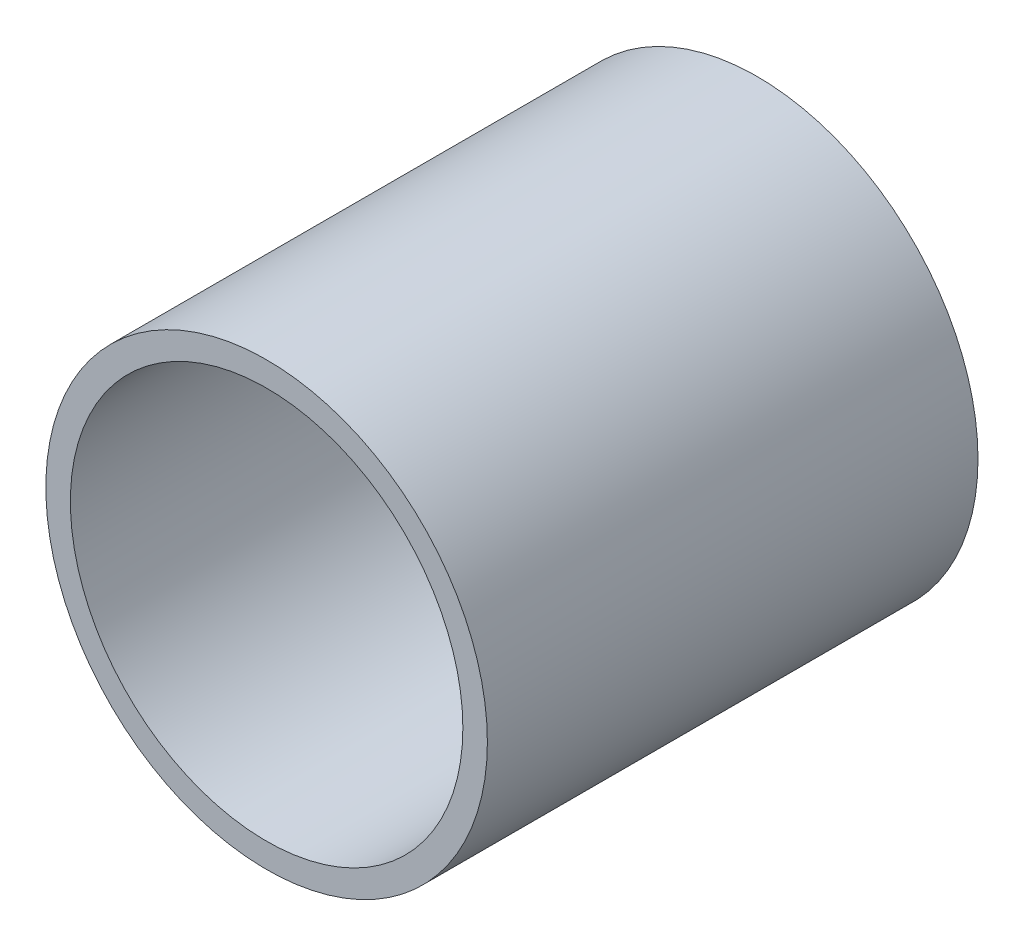
SolidWorks part; units mm, degrees
ref_plane "Front Plane" through (0, 0, 0) normal (0, 0, 1) x (1, 0, 0)
ref_plane "Top Plane" through (0, 0, 0) normal (0, 1, 0) x (1, 0, 0)
ref_plane "Right Plane" through (0, 0, 0) normal (1, 0, 0) x (0, 0, -1)
other "Configuration Table"
sketch "Sketch1" plane through (0, 0, 0) normal (0, 0, 1) x (1, 0, 0)
  circle A0 centre (0, 0) radius 8
  circle A1 centre (0, 0) radius 9
  dimension "D1" = 16
  dimension "D2" = 18
extrude "Boss-Extrude1" add sketch "Sketch1" along normal blind 20
